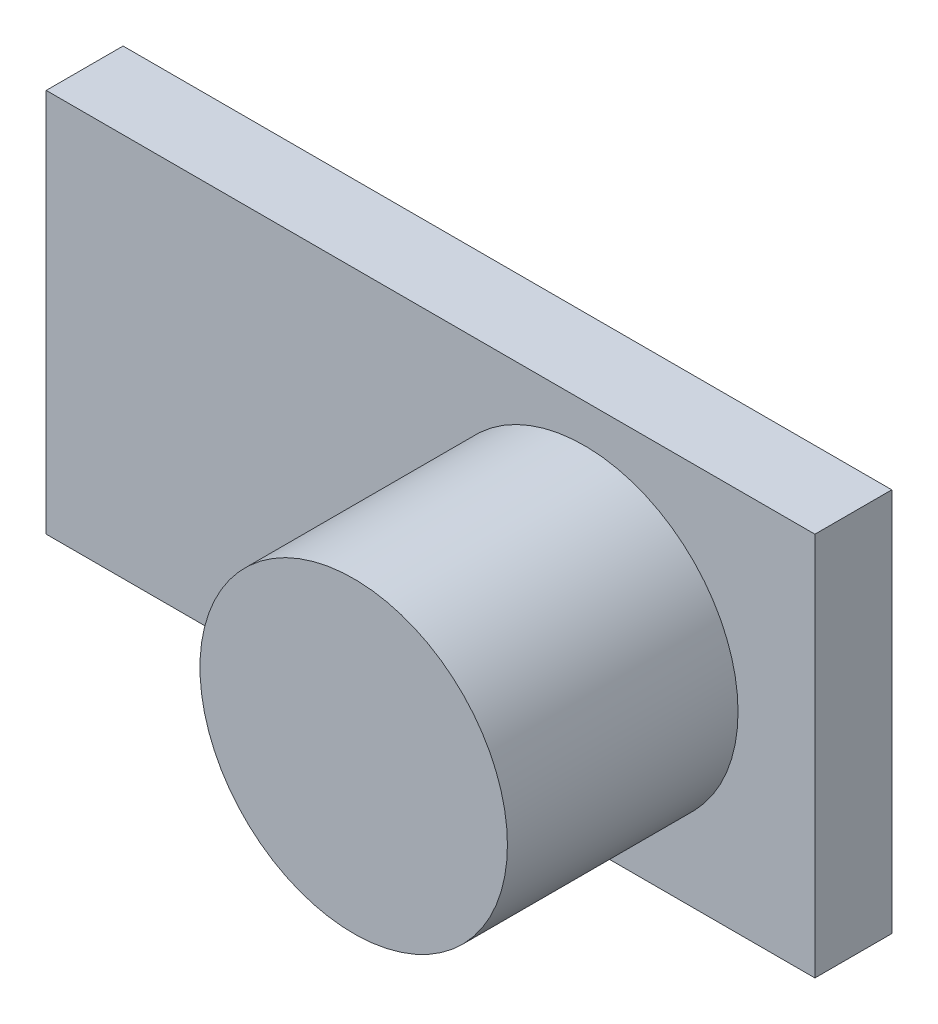
SolidWorks part; units mm, degrees
ref_plane "Front Plane" through (0, 0, 0) normal (0, 0, 1) x (1, 0, 0)
ref_plane "Top Plane" through (0, 0, 0) normal (0, 1, 0) x (1, 0, 0)
ref_plane "Right Plane" through (0, 0, 0) normal (1, 0, 0) x (0, 0, -1)
sketch "Sketch1" plane through (0, 0, 0) normal (0, 0, 1) x (1, 0, 0)
  line L0 (0, -61.6421) -> (0, 0) construction
  line L1 (-10, -22.0965) -> (10, -22.0965)
  line L2 (-10, -22.0965) -> (-10, -32.0965)
  line L3 (-10, -32.0965) -> (10, -32.0965)
  line L4 (10, -22.0965) -> (10, -32.0965)
  line L5 (-10, -27.0965) -> (10, -27.0965) construction
  ellipse E0 centre (0, -59.529) end of major axis (-5, -59.529) minor radius 2.1131 construction
  dimension "D1" = 10
  dimension "D2" = 20
  dimension "D3" = 10
extrude "Boss-Extrude1" add sketch "Sketch1" along normal blind 2
sketch "Sketch2" plane through (0, 0, 2) normal (0, 0, 1) x (1, 0, 0)
  line L0 (0, -22.0965) -> (0, -32.0965) construction
  line L1 (10, -22.0965) -> (-10, -22.0965) construction
  line L2 (-10, -32.0965) -> (10, -32.0965) construction
  line L3 (0, -27.0965) -> (9.9536, -27.0965) construction
  circle A0 centre (4, -27.0965) radius 4
extrude "Boss-Extrude2" add sketch "Sketch2" along normal blind 6
